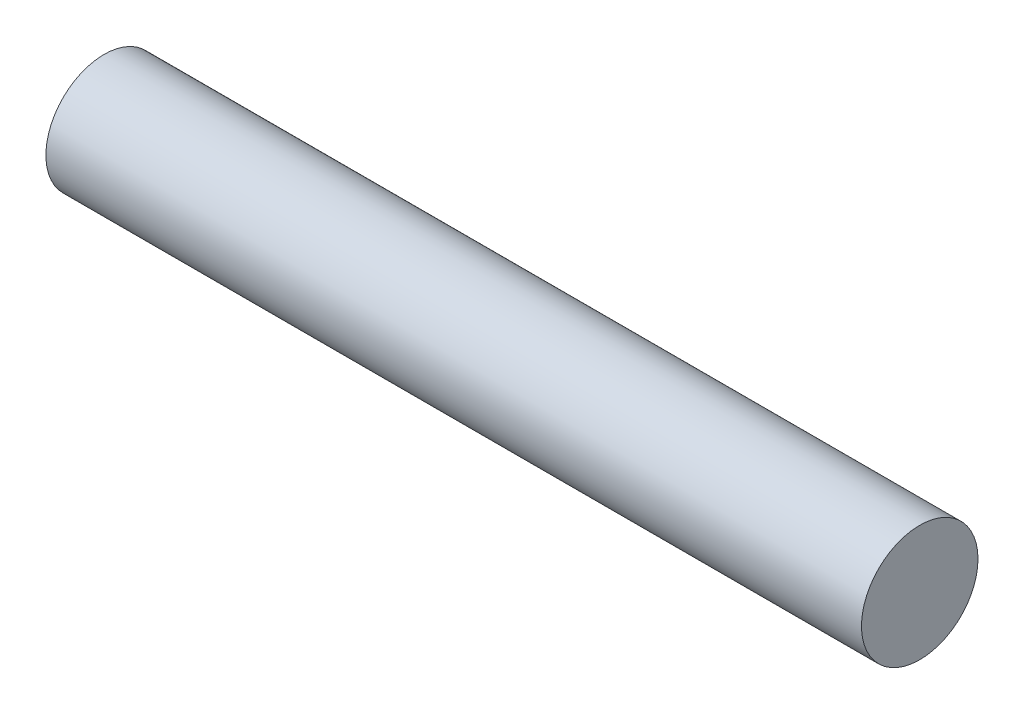
SolidWorks part; units mm, degrees
material "PETG"
ref_plane "Front Plane" through (0, 0, 0) normal (0, 0, 1) x (1, 0, 0)
ref_plane "Top Plane" through (0, 0, 0) normal (0, 1, 0) x (1, 0, 0)
ref_plane "Right Plane" through (0, 0, 0) normal (1, 0, 0) x (0, 0, -1)
sketch "Sketch1" plane through (0, 0, 0) normal (1, 0, 0) x (0, 0, -1)
  circle A0 centre (0, 0) radius 1
  dimension "D1" = 2
extrude "Boss-Extrude1" add sketch "Sketch1" along normal blind 14
ref_plane "Plane1" through (7, 0, 0) normal (1, 0, 0) x (0, 0, -1)
scale "Scale1" scale about origin uniform scaling yes scale factor 1
